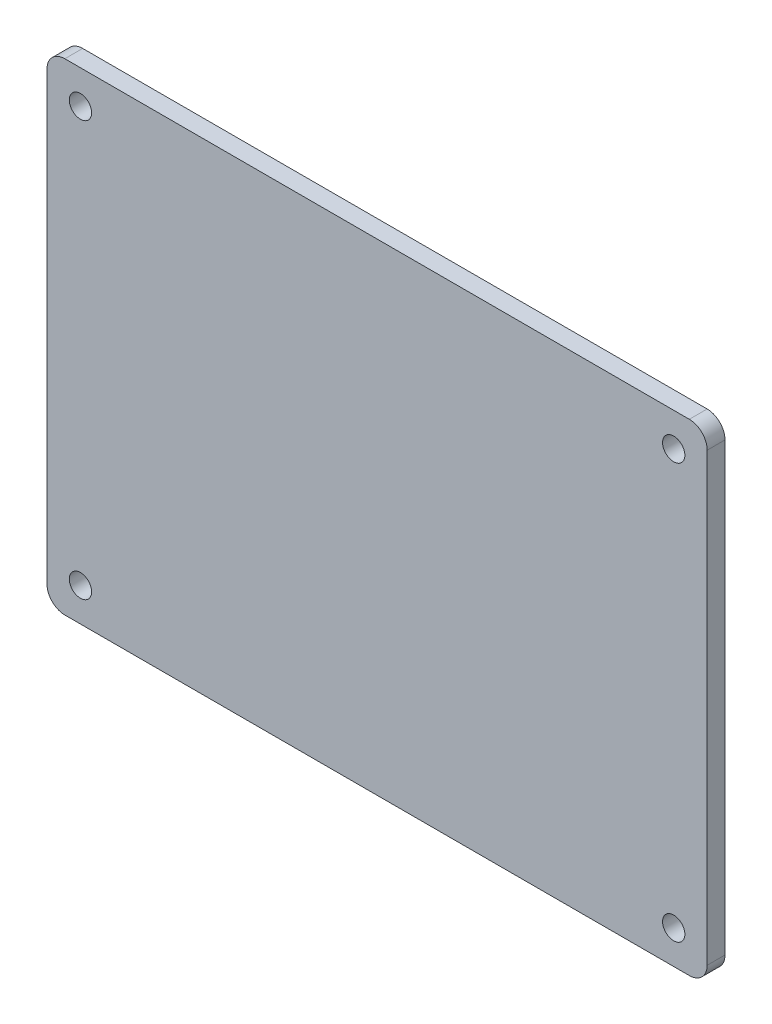
SolidWorks part; units mm, degrees
ref_plane "Front Plane" through (0, 0, 0) normal (0, 0, 1) x (1, 0, 0)
ref_plane "Top Plane" through (0, 0, 0) normal (0, 1, 0) x (1, 0, 0)
ref_plane "Right Plane" through (0, 0, 0) normal (1, 0, 0) x (0, 0, -1)
sketch "Sketch3" plane through (0, 0, 0) normal (0, 0, 1) x (1, 0, 0)
  line L1 (37, -27) -> (-37, -27)
  line L2 (37, -27) -> (37, 27)
  line L3 (37, 27) -> (-37, 27)
  line L4 (-37, -27) -> (-37, 27)
  line L5 (37, -27) -> (-37, 27) construction
  line L6 (37, 27) -> (-37, -27) construction
  point P0 (0, 0)
  dimension "D1" = 74
  dimension "D2" = 54
extrude "Boss-Extrude1" add sketch "Sketch3" along normal blind 2
sketch "Sketch4" plane through (0, 0, 0) normal (0, 0, -1) x (-1, 0, 0)
  line L1 (33.25, -23.25) -> (-33.25, -23.25) construction
  line L2 (33.25, -23.25) -> (33.25, 23.25) construction
  line L3 (33.25, 23.25) -> (-33.25, 23.25) construction
  line L4 (-33.25, -23.25) -> (-33.25, 23.25) construction
  line L5 (33.25, -23.25) -> (-33.25, 23.25) construction
  line L6 (33.25, 23.25) -> (-33.25, -23.25) construction
  circle A0 centre (-33.25, 23.25) radius 1.25
  circle A1 centre (33.25, 23.25) radius 1.25
  circle A2 centre (33.25, -23.25) radius 1.25
  circle A3 centre (-33.25, -23.25) radius 1.25
  point P0 (0, 0)
  dimension "D3" = 2.5
  dimension "D1" = 66.5
  dimension "D2" = 46.5
extrude "Cut-Extrude2" cut sketch "Sketch4" against normal up to next
fillet "Fillet1" radius 2 4 edges at (37, -27, 1) (37, 27, 1) (-37, 27, 1) (-37, -27, 1)
